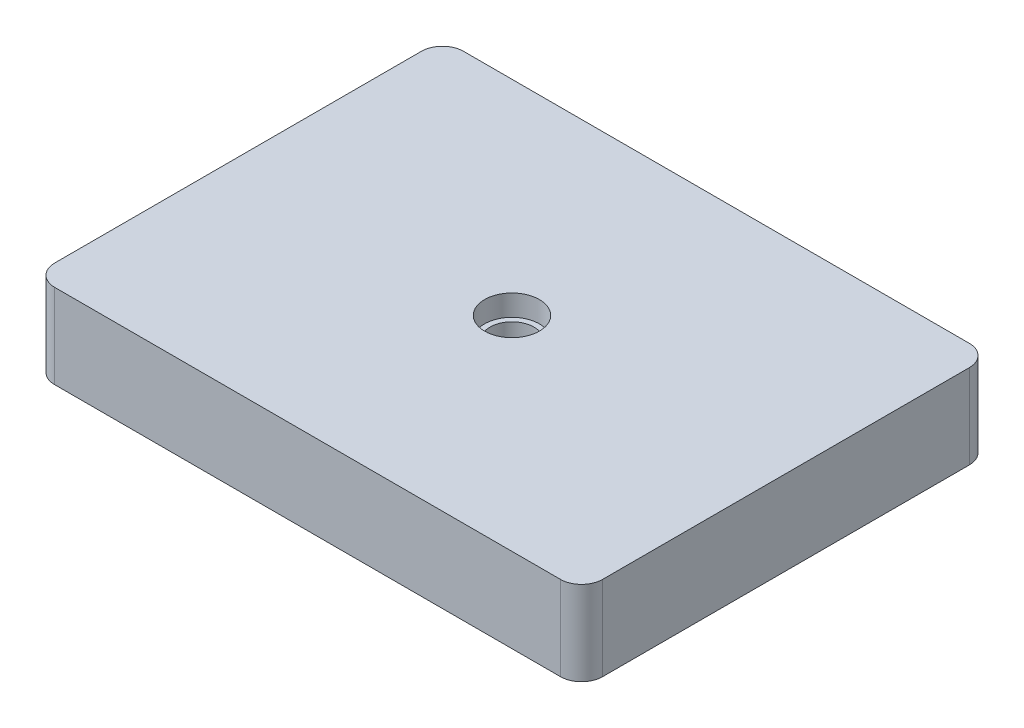
SolidWorks part; units mm, degrees
material "Plain Carbon Steel"
ref_plane "Front Plane" through (0, 0, 0) normal (0, 0, 1) x (1, 0, 0)
ref_plane "Top Plane" through (0, 0, 0) normal (0, 1, 0) x (1, 0, 0)
ref_plane "Right Plane" through (0, 0, 0) normal (1, 0, 0) x (0, 0, -1)
sketch "Sketch1" plane through (0, 0, 0) normal (0, 1, 0) x (1, 0, 0)
  line L1 (-65, -48.5) -> (65, -48.5)
  line L2 (-65, -48.5) -> (-65, 48.5)
  line L3 (-65, 48.5) -> (65, 48.5)
  line L4 (65, -48.5) -> (65, 48.5)
  line L5 (-65, -48.5) -> (65, 48.5) construction
  line L6 (-65, 48.5) -> (65, -48.5) construction
  point P0 (0, 0)
  dimension "D1" = 130
  dimension "D2" = 97
extrude "Boss-Extrude1" add sketch "Sketch1" against normal blind 20
sketch "Sketch2" plane through (0, 0, 0) normal (0, 1, 0) x (1, 0, 0)
  circle A0 centre (0, 0) radius 5.2
  dimension "D1" = 10.4
extrude "Cut-Extrude1" cut sketch "Sketch2" against normal through all
sketch "Sketch3" plane through (0, 0, 0) normal (0, 1, 0) x (1, 0, 0)
  circle A0 centre (0, 0) radius 6.5
  dimension "D1" = 13
extrude "Cut-Extrude2" cut sketch "Sketch3" against normal blind 5
fillet "Fillet1" radius 5 4 edges at (-65, -10, -48.5) (-65, -10, 48.5) (65, -10, -48.5) (65, -10, 48.5)
